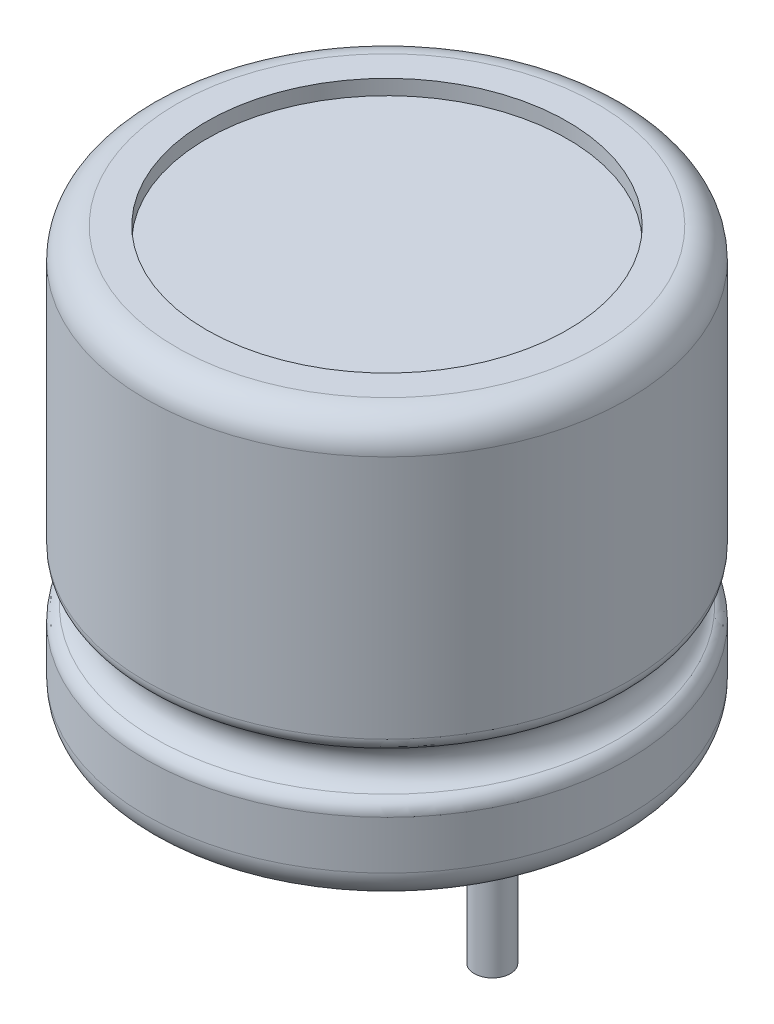
SolidWorks part; units mm, degrees
ref_plane "Front" through (0, 0, 0) normal (0, 0, 1) x (1, 0, 0)
ref_plane "Top" through (0, 0, 0) normal (0, 1, 0) x (1, 0, 0)
ref_plane "Right" through (0, 0, 0) normal (1, 0, 0) x (0, 0, -1)
sketch "草图1" plane through (0, 0, 0) normal (0, 0, 1) x (1, 0, 0)
  line L0 (4, 6.9906) -> (0, 6.9906)
  line L1 (0, 6.9906) -> (0, 0)
  line L2 (0, 0) -> (4, 0)
  line L3 (4, 0) -> (4, 1.5)
  line L4 (4, 2.2306) -> (4, 6.9906)
  line L5 (0, 6.9906) -> (0, 0) construction
  arc A0 (4, 1.5) -> (4, 2.2306) centre (4, 1.8653) cw
  dimension "D2" = 0.3653
  dimension "D1" = 1.5
  dimension "D3" = 4.76
  dimension "D4" = 4
revolve "旋转1" add sketch "草图1" angle 360 about L5
hole_wizard "Ø6.0 (6) 直径孔1" positions "草图3" profile "草图2" hole size "Ø6.0" standard "ANSI Metric"
sketch "草图3" plane through (0, 0, 0) normal (0, -1, 0) x (-1, 0, 0)
  point P0 (0, 0)
sketch "草图2" plane through (0, 0, 0) normal (1, 0, 0) x (0, 0, -1)
  line L0 (0, 0) -> (0, 0.25)
  line L1 (0, 0.25) -> (3, 0.25)
  line L2 (3, 0.25) -> (3, 0)
  line L5 (3, 0) -> (0, 0)
  line L10 (0, 0.25) -> (-3, 0.25) construction
  line L11 (0, -6.35) -> (0, 107.95) construction
  dimension "孔直径" = 6
  dimension "孔深度" = 0.25
  dimension "导头角度" = 180
ref_plane "基准面1" through (0, 0, 0) normal (0, 0, -1) x (-1, 0, 0)
sketch "草图4" plane through (0, 0, 0) normal (0, 0, -1) x (-1, 0, 0)
  line L1 (-1.75, -2.75) -> (-1.75, 0.25)
  line L2 (-1.75, 0.25) -> (-2.05, 0.25)
  line L3 (-2.05, 0.25) -> (-2.05, -2.75)
  line L4 (-1.75, -2.75) -> (-1.75, 0.25) construction
  line L5 (-1.75, -2.75) -> (-2.05, -2.75)
  line L6 (-4, 0.25) -> (4, 0.25) construction
  dimension "D1" = 3
revolve "旋转2" add sketch "草图4" angle 360 about L4
sketch "草图5" plane through (0, 0, 0) normal (0, 0, -1) x (-1, 0, 0)
  line L0 (1.45, -1.75) -> (1.75, -1.75)
  line L1 (1.75, -1.75) -> (1.75, 0.25)
  line L2 (1.75, 0.25) -> (1.45, 0.25)
  line L3 (1.45, 0.25) -> (1.45, -1.75)
  line L4 (1.75, -1.75) -> (1.75, 0.25) construction
  dimension "D1" = 2
revolve "旋转3" add sketch "草图5" angle 360 about L4
hole_wizard "Ø6.0 (6) 直径孔2" positions "草图7" profile "草图6" hole size "Ø6.0" standard "ANSI Metric"
sketch "草图7" plane through (0, 6.9906, 0) normal (0, 1, 0) x (1, 0, 0)
  point P0 (0, 0)
sketch "草图6" plane through (0, 6.9906, 0) normal (1, 0, 0) x (0, 0, 1)
  line L0 (0, 0) -> (0, 0.25)
  line L1 (0, 0.25) -> (3, 0.25)
  line L2 (3, 0.25) -> (3, 0)
  line L5 (3, 0) -> (0, 0)
  line L10 (0, 0.25) -> (-3, 0.25) construction
  line L11 (0, -6.35) -> (0, 107.95) construction
  dimension "孔直径" = 6
  dimension "孔深度" = 0.25
  dimension "导头角度" = 180
fillet "圆角1" radius 0.25 2 edges at (4, 2.2306, 0) (4, 1.5, 0)
fillet "圆角2" radius 0.5 2 edges at (4, 6.9906, 0) (4, 0, 0)
